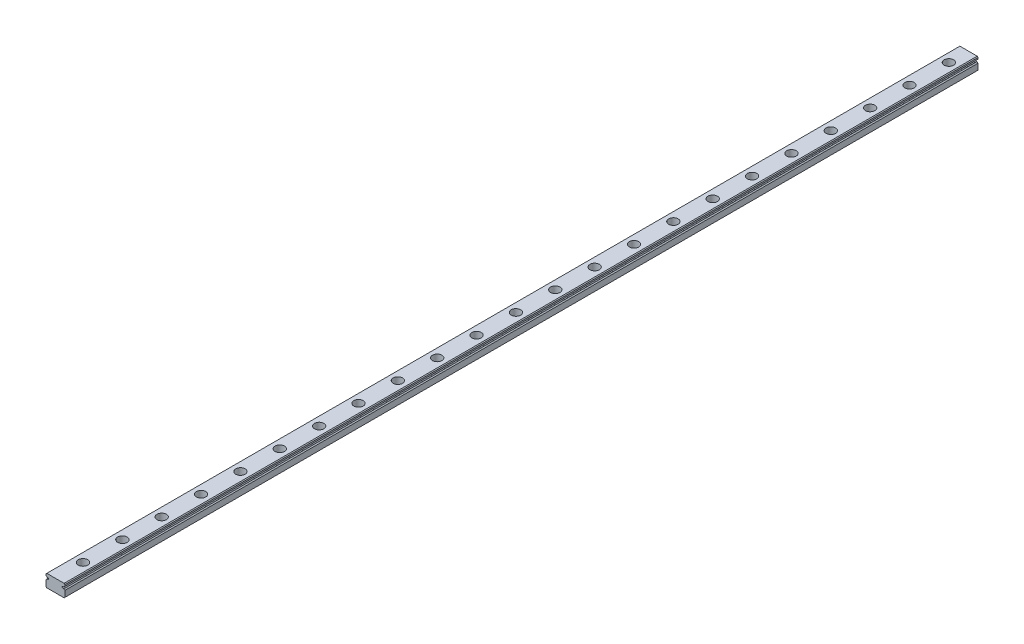
SolidWorks part; units mm, degrees
material "Chrome Stainless Steel"
ref_plane "Front Plane" through (0, 0, 0) normal (0, 0, 1) x (1, 0, 0)
ref_plane "Top Plane" through (0, 0, 0) normal (0, 1, 0) x (1, 0, 0)
ref_plane "Right Plane" through (0, 0, 0) normal (1, 0, 0) x (0, 0, -1)
sketch "Sketch1" plane through (0, 0, 0) normal (0, 0, 1) x (1, 0, 0)
  line L0 (0, 4) -> (0, -4) construction
  line L1 (5.5, -4) -> (-5.5, -4)
  line L2 (-5.5, -4) -> (-6, -3.5)
  line L3 (-6, -3.5) -> (-6, 0.3689)
  line L4 (5.5, 4) -> (-5.5, 4)
  line L5 (-5.5, 4) -> (-6, 3.5)
  line L6 (-6, 2.5511) -> (-6, 3.5)
  line L7 (-5.3839, 0.985) -> (-4.9211, 0.985)
  line L8 (-5.3839, 1.935) -> (-4.9211, 1.935)
  line L9 (5.3839, 0.985) -> (4.9211, 0.985)
  line L10 (5.5, 4) -> (6, 3.5)
  line L11 (6, 2.5511) -> (6, 3.5)
  line L12 (5.3839, 1.935) -> (4.9211, 1.935)
  line L13 (6, -3.5) -> (6, 0.3689)
  line L14 (5.5, -4) -> (6, -3.5)
  circle A0 centre (-6.475, 1.46) radius 1.19 construction
  circle A1 centre (-4.765, 1.46) radius 0.5 construction
  arc A2 (-6, 0.3689) -> (-5.3839, 0.985) centre (-6.475, 1.46) ccw
  arc A3 (-5.3839, 1.935) -> (-6, 2.5511) centre (-6.475, 1.46) ccw
  arc A4 (-4.9211, 0.985) -> (-4.9211, 1.935) centre (-4.765, 1.46) ccw
  arc A5 (5.3839, 1.935) -> (6, 2.5511) centre (6.475, 1.46) cw
  arc A6 (4.9211, 0.985) -> (4.9211, 1.935) centre (4.765, 1.46) cw
  arc A7 (6, 0.3689) -> (5.3839, 0.985) centre (6.475, 1.46) cw
  point P4 (0, 0)
  dimension "D5" = 5.46
  dimension "D6" = 6.475
  dimension "D7" = 2.38
  dimension "D11" = 1
  dimension "D12" = 5.46
  dimension "D13" = 4.765
  dimension "D1" = 8
  dimension "D2" = 0.5
  dimension "D3" = 0.5
  dimension "D4" = 6
  dimension "D8" = 0.5
  dimension "D9" = 0.5
  dimension "D10" = 6
  dimension "D14" = 0.475
  dimension "D15" = 0.475
extrude "Boss-Extrude1" add sketch "Sketch1" along normal blind 580 contours L13 A7 L9 A6 L12 A5 L11 L10 L4 L5 L6 A3 L8 A4 L7 A2 L3 L2 L1 L14
sketch "Sketch2" plane through (0, 4, 0) normal (0, 1, 0) x (1, 0, 0)
  line L0 (5.5, 0) -> (-5.5, 0) construction
  circle A0 centre (0, -12.5) radius 3
  dimension "D1" = 12.5
extrude "Cut-Extrude1" cut sketch "Sketch2" against normal blind 4.5
sketch "Sketch3" plane through (0, -0.5, 0) normal (0, 1, 0) x (1, 0, 0)
  circle A0 centre (0, -12.5) radius 1.75
extrude "Cut-Extrude2" cut sketch "Sketch3" against normal through all
pattern_linear "LPattern1" count 23 spacing 25 along (0, 0, 1) of "Cut-Extrude1", "Cut-Extrude2"
